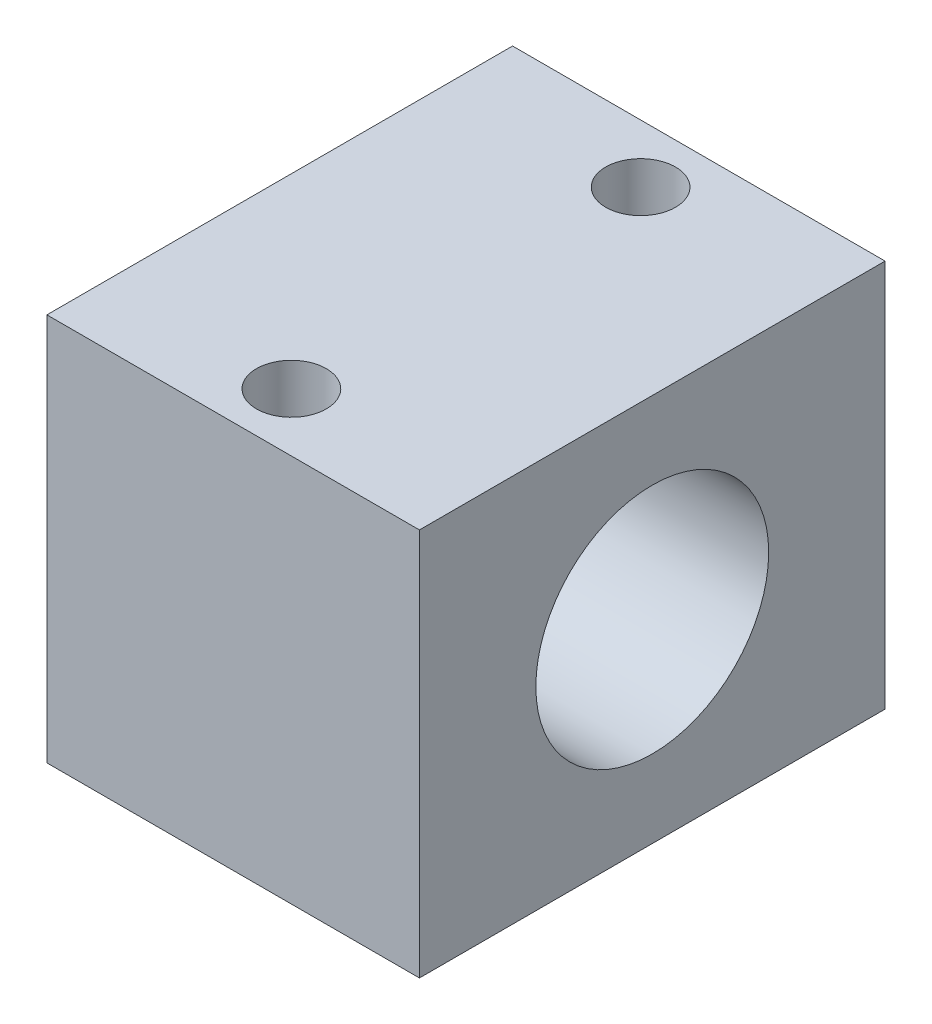
SolidWorks part; units mm, degrees
ref_plane "Alzado" through (0, 0, 0) normal (0, 0, 1) x (1, 0, 0)
ref_plane "Planta" through (0, 0, 0) normal (0, 1, 0) x (1, 0, 0)
ref_plane "Vista lateral" through (0, 0, 0) normal (1, 0, 0) x (0, 0, -1)
sketch "Croquis1" plane through (0, 0, 0) normal (1, 0, 0) x (0, 0, -1)
  line L0 (19.241, 16.5227) -> (-10.759, 16.5227)
  line L1 (-10.759, 16.5227) -> (-10.759, -8.4773)
  line L2 (-10.759, -8.4773) -> (19.241, -8.4773)
  line L3 (19.241, -8.4773) -> (19.241, 16.5227)
  dimension "D1" = 30
  dimension "D2" = 25
extrude "Saliente-Extruir1" add sketch "Croquis1" along normal blind 24
sketch "Croquis2" plane through (0, 0, 0) normal (-1, 0, 0) x (0, 0, 1)
  line L1 (-19.241, 4.0227) -> (10.759, 4.0227) construction
  line L2 (-19.241, -8.4773) -> (-19.241, 16.5227) construction
  line L3 (10.759, 16.5227) -> (10.759, -8.4773) construction
  line L4 (-4.241, 16.5227) -> (-4.241, -8.4773) construction
  line L5 (-19.241, 16.5227) -> (10.759, 16.5227) construction
  line L6 (10.759, -8.4773) -> (-19.241, -8.4773) construction
  circle A0 centre (-4.241, 4.0227) radius 7.5
extrude "Cortar-Extruir1" cut sketch "Croquis2" against normal blind 24
sketch "Croquis4" plane through (0, 16.5227, 0) normal (0, 1, 0) x (1, 0, 0)
  line L0 (12, 19.241) -> (12, -10.759) construction
  line L1 (24, 19.241) -> (0, 19.241) construction
  line L2 (24, -10.759) -> (0, -10.759) construction
  circle A0 centre (12, 15.491) radius 2.25
  circle A1 centre (12, -7.009) radius 2.25
  dimension "D1" = 3.75
  dimension "D3" = 4.5
  dimension "D4" = 4.5
  dimension "D2" = 3.75
extrude "Cortar-Extruir4" cut sketch "Croquis4" against normal up to next
